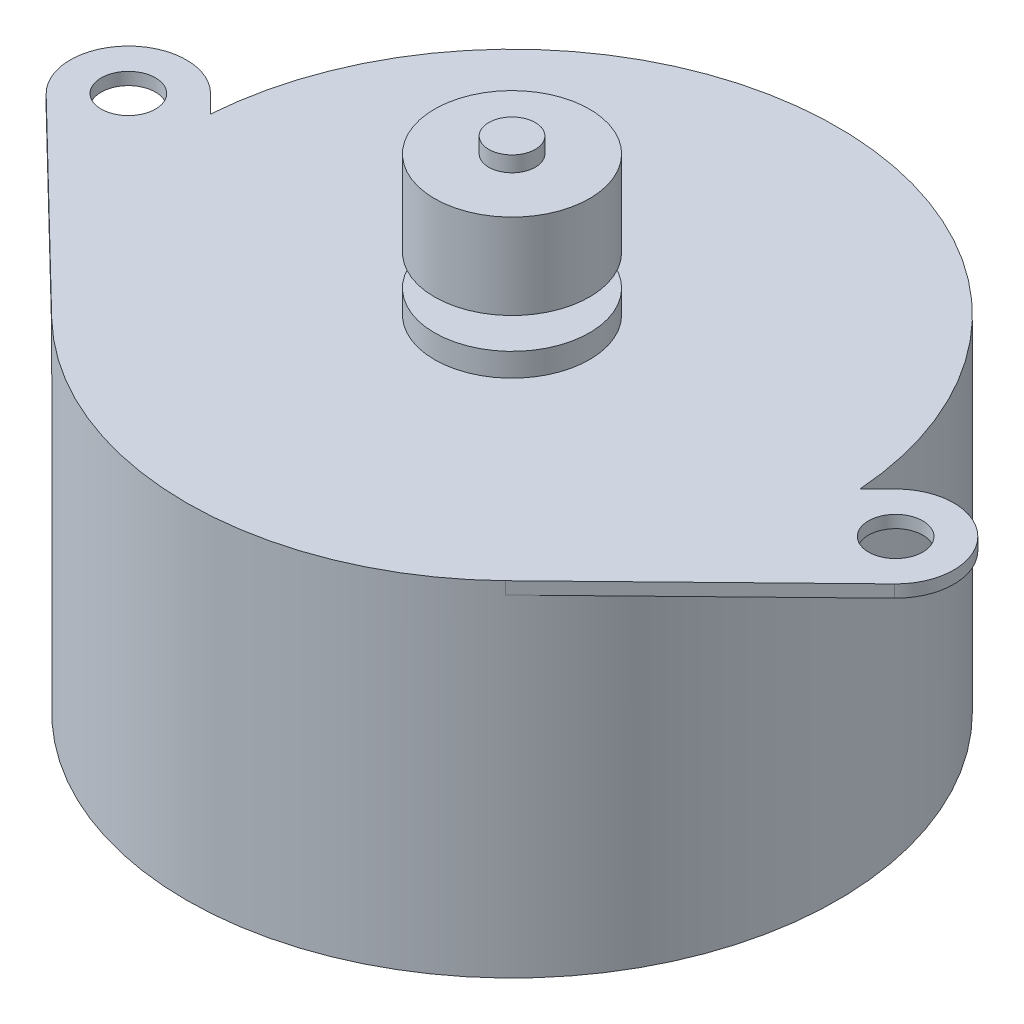
SolidWorks part; units mm, degrees
ref_plane "Alzado" through (0, 0, 0) normal (0, 0, 1) x (1, 0, 0)
ref_plane "Planta" through (0, 0, 0) normal (0, 1, 0) x (1, 0, 0)
ref_plane "Vista lateral" through (0, 0, 0) normal (1, 0, 0) x (0, 0, -1)
sketch "Croquis1" plane through (0, 0, 0) normal (0, 1, 0) x (1, 0, 0)
  circle A0 centre (0, 0) radius 21
  dimension "D1" = 42
extrude "Saliente-Extruir1" add sketch "Croquis1" along normal blind 21.4
sketch "Croquis2" plane through (0, 21.4, 0) normal (0, 1, 0) x (1, 0, 0)
  line L1 (-27.3634, -2.6918) -> (-14.6349, -15.0606)
  line L2 (-22.1012, 2.652) -> (-20.9464, 1.4997)
  line L3 (27.3634, -2.6911) -> (14.6353, -15.0601)
  line L4 (22.1004, 2.6519) -> (20.9464, 1.4997)
  arc A0 (-14.6349, -15.0606) -> (14.6353, -15.0601) centre (0, 0) ccw
  arc A1 (27.3634, -2.6911) -> (22.1004, 2.6519) centre (24.75, -0.0017) ccw
  circle A2 centre (24.75, -0.0017) radius 1.75
  arc A3 (-22.1012, 2.652) -> (-27.3634, -2.6918) centre (-24.75, -0.0025) ccw
  circle A4 centre (-24.75, -0.0025) radius 1.75
  arc A5 (20.9464, 1.4997) -> (-20.9464, 1.4997) centre (0, 0) ccw
  dimension "D1" = 7.5
  dimension "D2" = 24.75
  dimension "D3" = 7.5
  dimension "D6" = 3.5
  dimension "D4" = 24.75
extrude "Saliente-Extruir2" add sketch "Croquis2" along normal blind 0.8
sketch "Croquis3" plane through (0, 22.2, 0) normal (0, 1, 0) x (1, 0, 0)
  circle A0 centre (0, 0) radius 5
  dimension "D1" = 10
extrude "Saliente-Extruir3" add sketch "Croquis3" along normal blind 1.5
sketch "Croquis4" plane through (0, 23.7, 0) normal (0, 1, 0) x (1, 0, 0)
  circle A0 centre (0, 0) radius 1.5
extrude "Saliente-Extruir4" add sketch "Croquis4" along normal blind 8.5
ref_plane "Plano1" through (0, 25.7, 0) normal (0, 1, 0) x (1, 0, 0)
sketch "Croquis5" plane through (0, 25.7, 0) normal (0, 1, 0) x (1, 0, 0)
  circle A0 centre (0, 0) radius 5
  circle A1 centre (0, 0) radius 1.5
  dimension "D1" = 10
extrude "Saliente-Extruir5" add sketch "Croquis5" along normal blind 5.5
sketch "Croquis6" plane through (0, 0, 0) normal (0, -1, 0) x (1, 0, 0)
  circle A0 centre (0, 0) radius 1.5
extrude "Saliente-Extruir6" add sketch "Croquis6" along normal blind 1
